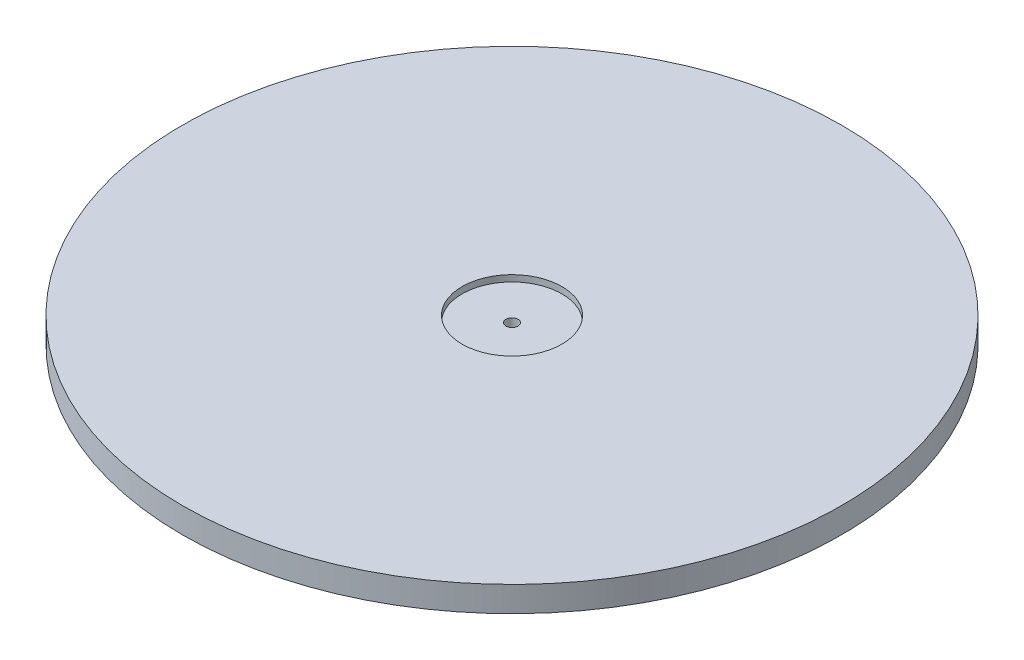
SolidWorks part; units mm, degrees
ref_plane "Front Plane" through (0, 0, 0) normal (0, 0, 1) x (1, 0, 0)
ref_plane "Top Plane" through (0, 0, 0) normal (0, 1, 0) x (1, 0, 0)
ref_plane "Right Plane" through (0, 0, 0) normal (1, 0, 0) x (0, 0, -1)
sketch "Sketch1" plane through (0, 0, 0) normal (0, 1, 0) x (1, 0, 0)
  circle A0 centre (0, 0) radius 165.1
  circle A1 centre (0, 0) radius 3
  dimension "D1" = 330.2
  dimension "D2" = 6
extrude "Boss-Extrude1" add sketch "Sketch1" along normal blind 12.7
sketch "Sketch5" plane through (0, 12.7, 0) normal (0, 1, 0) x (1, 0, 0)
  circle A1 centre (0, 0) radius 165.1
  circle A2 centre (0, 0) radius 165.1
  dimension "D1" = 0
sketch "Sketch7" plane through (0, 12.7, 0) normal (0, 1, 0) x (1, 0, 0)
  circle A0 centre (0, 0) radius 3 construction
  circle A1 centre (0, 0) radius 165.1 construction
  circle A2 centre (0, 0) radius 3
  circle A3 centre (0, 0) radius 165.1
extrude "Boss-Extrude3" add sketch "Sketch7" along normal blind 6.35
sketch "Sketch8" plane through (0, 19.05, 0) normal (0, 1, 0) x (1, 0, 0)
  circle A0 centre (0, 0) radius 25
  dimension "D1" = 50
extrude "Cut-Extrude1" cut sketch "Sketch8" against normal blind 6.35
sketch "Sketch9" plane through (0, 0, 0) normal (0, -1, 0) x (1, 0, 0)
  circle A0 centre (0, 0) radius 25
  dimension "D1" = 50
extrude "Cut-Extrude2" cut sketch "Sketch9" against normal blind 6.35
sketch "Sketch10" plane through (0, 0, 0) normal (0, -1, 0) x (1, 0, 0)
  circle A1 centre (0, 0) radius 165.1
  circle A2 centre (0, 0) radius 165.1
  dimension "D1" = 0
extrude "Cut-Extrude3" cut sketch "Sketch10" against normal blind 6.35
sketch "Sketch11" plane through (0, 6.35, 0) normal (0, -1, 0) x (1, 0, 0)
  circle A0 centre (0, 0) radius 25
  dimension "D1" = 50
extrude "Cut-Extrude5" cut sketch "Sketch11" against normal blind 3.175
sketch "Sketch12" plane through (0, 12.7, 0) normal (0, 1, 0) x (1, 0, 0)
  circle A1 centre (0, 0) radius 25
  circle A2 centre (0, 0) radius 25
  dimension "D1" = 0
extrude "Boss-Extrude4" add sketch "Sketch12" along normal blind 3.175
sketch "Sketch13" plane through (0, 12.7, 0) normal (0, -1, 0) x (1, 0, 0)
  circle A0 centre (0, 0) radius 3 construction
  circle A1 centre (0, 0) radius 3
extrude "Cut-Extrude6" cut sketch "Sketch13" against normal blind 3.175
